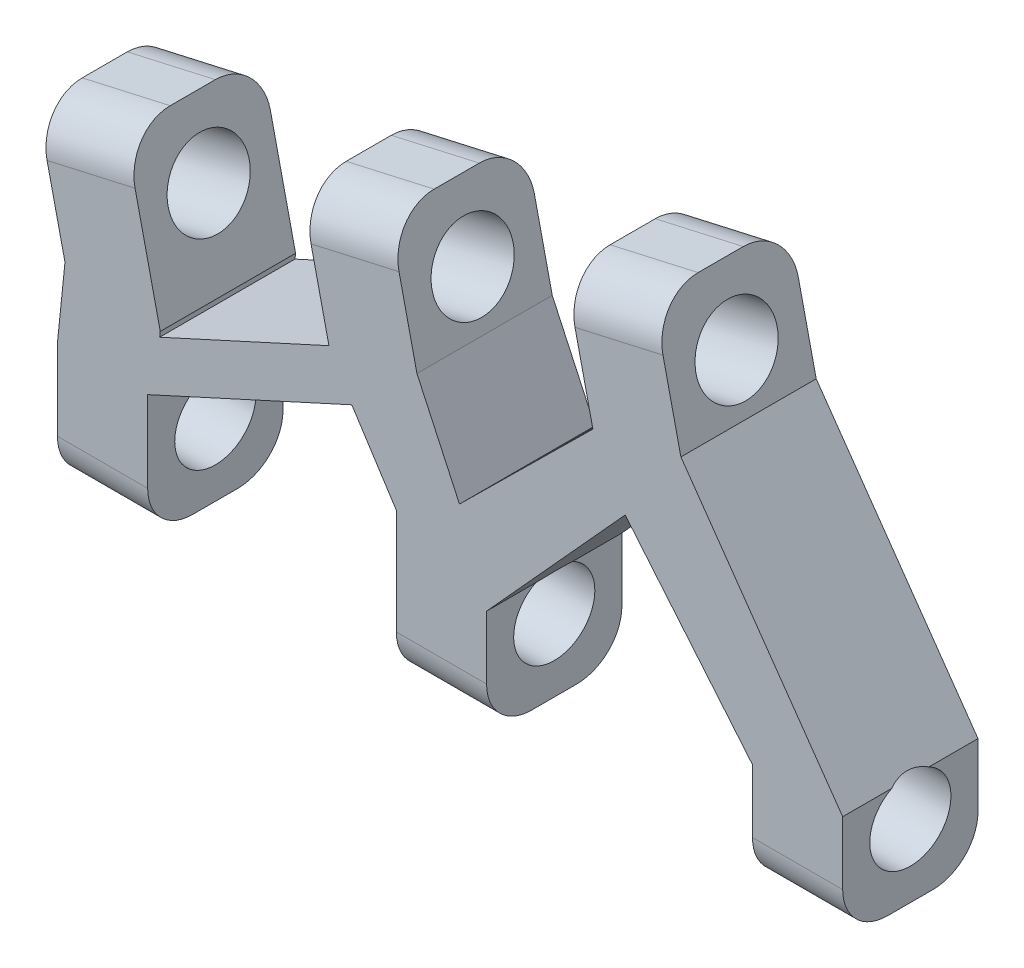
SolidWorks part; units mm, degrees
ref_plane "Front Plane" through (0, 0, 0) normal (0, 0, 1) x (1, 0, 0)
ref_plane "Top Plane" through (0, 0, 0) normal (0, 1, 0) x (1, 0, 0)
ref_plane "Right Plane" through (0, 0, 0) normal (1, 0, 0) x (0, 0, -1)
sketch "Sketch2" plane through (0, 0, 0) normal (0, 0, 1) x (1, 0, 0)
  line L0 (-216.0191, 17.3828) -> (-212.9301, 3.7279)
  line L2 (-202.3695, 2.3668) -> (-206.2655, 19.5893)
  line L3 (-206.2655, 19.5893) -> (-216.0191, 17.3828)
  line L4 (-110.7389, 36.0728) -> (-234.6089, 8.0511) construction
  line L5 (-213.764, -4.3984) -> (-213.764, -18.3984)
  line L6 (-233.947, 5.125) -> (-156.3435, 22.6804) construction
  line L7 (-186.7585, 24.0021) -> (-183.6694, 10.3472)
  line L9 (-173.9159, 12.5536) -> (-177.0049, 26.2086)
  line L10 (-177.0049, 26.2086) -> (-186.7585, 24.0021)
  line L11 (-157.4978, 30.6214) -> (-154.4088, 16.9665)
  line L13 (-144.6553, 19.1729) -> (-147.7443, 32.8279)
  line L14 (-147.7443, 32.8279) -> (-157.4978, 30.6214)
  line L15 (-213.764, -10.3984) -> (-118.0115, -10.3984) construction
  line L16 (-213.764, -18.3984) -> (-203.764, -18.3984)
  line L21 (-203.764, -18.3984) -> (-203.764, -4.3984)
  line L24 (-176.1945, -1.7291) -> (-176.1945, -18.3984)
  line L25 (-176.1945, -18.3984) -> (-166.1945, -18.3984)
  line L26 (-166.1945, -6.3984) -> (-166.1945, -18.3984)
  line L28 (-136.7206, -6.3984) -> (-136.7206, -18.3984)
  line L29 (-136.7206, -18.3984) -> (-126.7206, -18.3984)
  line L30 (-126.7206, -6.3984) -> (-126.7206, -18.3984)
  line L31 (-228.6463, -13.3984) -> (-112.1463, -13.3984) construction
  line L32 (-212.9301, 3.7279) -> (-213.764, -4.3984)
  line L33 (-202.3695, 2.3668) -> (-202.434, 1.7772)
  line L34 (-173.9159, 12.5536) -> (-169.2015, 2.3732)
  line L35 (-144.6553, 19.1729) -> (-126.7206, -6.3984)
  line L36 (-150.8284, 10.5186) -> (-136.7206, -6.3984)
  line L37 (-150.8284, 10.5186) -> (-166.1945, -6.3984)
  line L38 (-154.4088, 16.9665) -> (-169.2015, 2.3732)
  line L40 (-176.1945, -1.7291) -> (-181.1361, 5.936)
  line L42 (-181.1361, 5.936) -> (-203.764, -4.3984)
  line L43 (-183.6694, 10.3472) -> (-202.434, 1.7772)
  point P8 (-204.3175, 10.978)
  point P26 (-208.764, -10.3984)
  dimension "D1" = 5
  dimension "D3" = 10
  dimension "D4" = 5
  dimension "D5" = 5
  dimension "D6" = 20
  dimension "D7" = 10
  dimension "D8" = 20
  dimension "D9" = 10
  dimension "D10" = 10
  dimension "D13" = 10
  dimension "D15" = 10
  dimension "D16" = 5
  dimension "D17" = 5
extrude "Boss-Extrude1" add sketch "Sketch2" along normal blind 15
sketch "Sketch3" plane through (-201.7616, -45.6423, 0) normal (-0.9754, -0.2206, 0) x (0, 0, 1)
  line L0 (15, 64.6176) -> (0, 64.6176) construction
  line L1 (15, 59.6176) -> (20.8792, 59.6176)
  line L3 (15, 50.6176) -> (0, 50.6176) construction
  line L4 (5, 64.6176) -> (8.8598, 64.6176)
  line L10 (10, 64.6176) -> (8.8598, 64.6176)
  line L11 (0, 59.6176) -> (-2.562, 59.6176)
  line L12 (-2.562, 59.6176) -> (-2.562, 67.7911)
  line L13 (-2.562, 67.7911) -> (14.3726, 67.7911)
  line L16 (20.8792, 59.6176) -> (20.8792, 67.7911)
  line L17 (20.8792, 67.7911) -> (14.3726, 67.7911)
  circle A0 centre (7.5, 56.6176) radius 4.5
  arc A4 (5, 64.6176) -> (0, 59.6176) centre (5, 59.6176) ccw
  arc A5 (10, 64.6176) -> (15, 59.6176) centre (10, 59.6176) cw
  point P2 (0, 0)
  point P5 (7.5, 64.6176)
  point P15 (15, 64.6176)
  point P18 (15, 64.6176)
  point P19 (0, 64.6176)
  point P21 (0, 64.6176)
  point P25 (15, 64.6176)
  dimension "D1" = 9
  dimension "D2" = 5
  dimension "D3" = 6
sketch "Sketch4" plane through (-213.764, 0, 0) normal (-1, 0, 0) x (0, 0, 1)
  line L2 (15, -4.3984) -> (0, -4.3984) construction
  line L10 (5, -18.3984) -> (10, -18.3984)
  line L12 (-2.6566, -13.3984) -> (0, -13.3984)
  line L13 (-2.6566, -13.3984) -> (-2.6566, -22.0253)
  line L14 (-2.6566, -22.0253) -> (20.1932, -22.0253)
  line L15 (20.1932, -22.0253) -> (20.1932, -13.3984)
  line L16 (20.1932, -13.3984) -> (15, -13.3984)
  circle A0 centre (7.5, -10.3984) radius 4.5
  arc A3 (10, -18.3984) -> (15, -13.3984) centre (10, -13.3984) ccw
  arc A4 (5, -18.3984) -> (0, -13.3984) centre (5, -13.3984) cw
  point P14 (7.5, -4.3984)
  point P18 (12, -16.3984)
  point P20 (15, -18.3984)
  point P24 (0, -18.3984)
  dimension "D1" = 9
  dimension "D2" = 5
  dimension "D3" = 6
extrude "Cut-Extrude1" cut sketch "Sketch3" against normal through all
extrude "Cut-Extrude2" cut sketch "Sketch4" against normal through all
